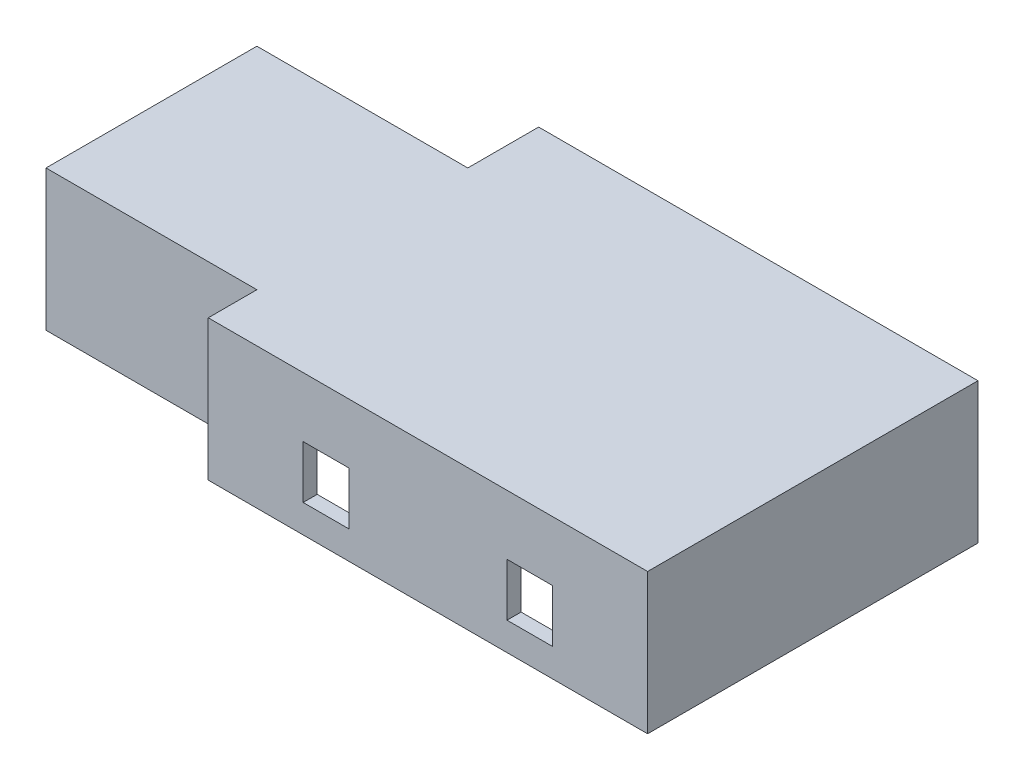
SolidWorks part; units mm, degrees
ref_plane "Front Plane" through (0, 0, 0) normal (0, 0, 1) x (1, 0, 0)
ref_plane "Top Plane" through (0, 0, 0) normal (0, 1, 0) x (1, 0, 0)
ref_plane "Right Plane" through (0, 0, 0) normal (1, 0, 0) x (0, 0, -1)
sketch "Sketch1" plane through (0, 0, 0) normal (0, 1, 0) x (1, 0, 0)
  line L1 (-51.0787, 32.8363) -> (73.9213, 32.8363)
  line L2 (-51.0787, 32.8363) -> (-51.0787, -61.1637)
  line L3 (-51.0787, -61.1637) -> (73.9213, -61.1637)
  line L4 (73.9213, 32.8363) -> (73.9213, -61.1637)
  dimension "D1" = 125
  dimension "D2" = 94
extrude "Boss-Extrude1" add sketch "Sketch1" along normal blind 40
sketch "Sketch2" plane through (0, 0, 0) normal (0, 1, 0) x (1, 0, 0)
  line L0 (73.9213, -61.1637) -> (73.9213, 32.8363) construction
  line L1 (-44.3699, 28.8363) -> (69.9213, 28.8363)
  line L2 (-44.3699, 28.8363) -> (-44.3699, -57.1637)
  line L3 (-44.3699, -57.1637) -> (69.9213, -57.1637)
  line L4 (69.9213, 28.8363) -> (69.9213, -57.1637)
  line L5 (73.9213, 32.8363) -> (-51.0787, 32.8363) construction
  line L6 (-51.0787, 32.8363) -> (-51.0787, -61.1637) construction
  line L7 (-51.0787, -61.1637) -> (73.9213, -61.1637) construction
  dimension "D1" = 4
  dimension "D2" = 114.2912
  dimension "D3" = 4
  dimension "D4" = 6.7088
  dimension "D5" = 4
extrude "Cut-Extrude1" cut sketch "Sketch2" along normal blind 30
sketch "Sketch3" plane through (0, 0, 0) normal (0, 0, 1) x (1, 0, 0)
  line L0 (-51.0787, 0) -> (73.9213, 0) construction
  line L1 (-24.0787, 23) -> (-11.0787, 23)
  line L2 (-24.0787, 23) -> (-24.0787, 8)
  line L3 (-24.0787, 8) -> (-11.0787, 8)
  line L4 (-11.0787, 23) -> (-11.0787, 8)
  line L5 (-51.0787, 40) -> (-51.0787, 0) construction
  line L6 (33.9213, 23) -> (46.9213, 23)
  line L7 (33.9213, 23) -> (33.9213, 8)
  line L8 (33.9213, 8) -> (46.9213, 8)
  line L9 (46.9213, 23) -> (46.9213, 8)
  line L10 (73.9213, 40) -> (73.9213, 0) construction
  dimension "D1" = 13
  dimension "D2" = 15
  dimension "D3" = 8
  dimension "D4" = 27
  dimension "D5" = 8
  dimension "D6" = 27
  dimension "D7" = 27
  dimension "D8" = 13
  dimension "D9" = 15
extrude "Cut-Extrude2" cut sketch "Sketch3" against normal blind 10 from surface at 61.1637 starting at face at (11.4213, 20, 61.1637)
sketch "Sketch4" plane through (0, 0, 0) normal (0, 1, 0) x (1, 0, 0)
  circle A0 centre (-43.223, -55.9165) radius 4
  circle A1 centre (68.118, -55.9165) radius 4
  circle A2 centre (68.118, 26.8195) radius 4
  circle A3 centre (-43.223, 26.8195) radius 4
  dimension "D1" = 8
  dimension "D2" = 8
  dimension "D3" = 8
  dimension "D4" = 8
extrude "Boss-Extrude2" add sketch "Sketch4" along normal blind 20
sketch "Sketch5" plane through (0, 0, 0) normal (0, 1, 0) x (1, 0, 0)
  circle A0 centre (-43.8643, -56.0448) radius 2
  circle A1 centre (67.9897, -56.0448) radius 2
  circle A2 centre (68.118, 26.8195) radius 2
  circle A3 centre (-43.8643, 26.8195) radius 2
  dimension "D1" = 4
  dimension "D2" = 4
  dimension "D3" = 4
  dimension "D4" = 4
extrude "Cut-Extrude3" cut sketch "Sketch5" along normal blind 15
sketch "Sketch6" plane through (0, 0, 0) normal (0, 0, 1) x (1, 0, 0)
  line L0 (73.9213, 40) -> (-51.0787, 40) construction
  line L1 (33.9213, 26) -> (-11.0787, 26)
  line L2 (33.9213, 26) -> (33.9213, 14)
  line L3 (33.9213, 14) -> (-11.0787, 14)
  line L4 (-11.0787, 26) -> (-11.0787, 14)
  line L5 (73.9213, 0) -> (-51.0787, 0) construction
  line L6 (-51.0787, 40) -> (-51.0787, 0) construction
  line L7 (73.9213, 40) -> (73.9213, 0) construction
  dimension "D1" = 14
  dimension "D2" = 14
  dimension "D3" = 40
  dimension "D4" = 40
extrude "Cut-Extrude4" cut sketch "Sketch6" along normal blind 10 from surface at -38.8363
sketch "Sketch7" plane through (0, 0, 0) normal (0, 1, 0) x (1, 0, 0)
  line L0 (-51.0787, 32.8363) -> (-51.0787, -61.1637) construction
  line L1 (-111.0787, 12.6777) -> (-51.0787, 12.6777)
  line L2 (-111.0787, 12.6777) -> (-111.0787, -47.3223)
  line L3 (-111.0787, -47.3223) -> (-51.0787, -47.3223)
  line L4 (-51.0787, 12.6777) -> (-51.0787, -47.3223)
  dimension "D1" = 60
  dimension "D2" = 60
extrude "Boss-Extrude3" add sketch "Sketch7" along normal blind 40
sketch "Sketch8" plane through (0, 0, 0) normal (0, 1, 0) x (1, 0, 0)
  line L0 (-44.3699, 22.9875) -> (-44.3699, -52.0845) construction
  line L1 (-44.3699, 5.8648) -> (-106.6663, 5.8648)
  line L2 (-44.3699, 5.8648) -> (-44.3699, -41.9758)
  line L3 (-44.3699, -41.9758) -> (-106.6663, -41.9758)
  line L4 (-106.6663, 5.8648) -> (-106.6663, -41.9758)
extrude "Cut-Extrude5" cut sketch "Sketch8" along normal blind 30
